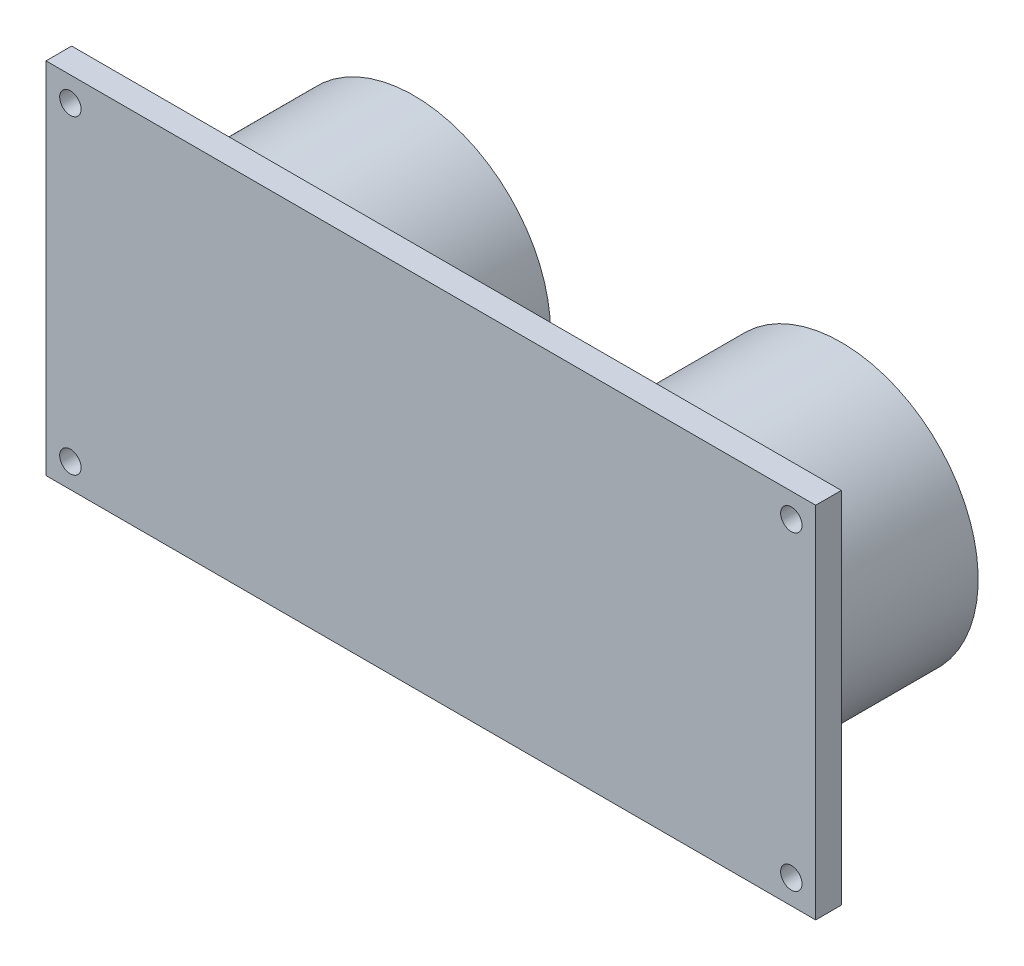
SolidWorks part; units mm, degrees
ref_plane "Alzado" through (0, 0, 0) normal (0, 0, 1) x (1, 0, 0)
ref_plane "Planta" through (0, 0, 0) normal (0, 1, 0) x (1, 0, 0)
ref_plane "Vista lateral" through (0, 0, 0) normal (1, 0, 0) x (0, 0, -1)
sketch "Croquis1" plane through (0, 0, 0) normal (0, 0, 1) x (1, 0, 0)
  line L0 (0.8, 0.8) -> (44.2, 0.8) construction
  line L1 (0, 0) -> (45, 0)
  line L2 (0, 0) -> (0, 21)
  line L3 (0, 21) -> (45, 21)
  line L4 (45, 0) -> (45, 21)
  line L5 (44.2, 0.8) -> (44.2, 20.2) construction
  line L6 (0.8, 20.2) -> (44.2, 20.2) construction
  line L7 (0.8, 0.8) -> (0.8, 20.2) construction
  line L8 (22.5, 21) -> (22.5, 0) construction
  line L9 (0, 10.5) -> (45, 10.5) construction
  circle A0 centre (1.425, 19.575) radius 0.625
  circle A1 centre (43.575, 19.575) radius 0.625
  circle A2 centre (43.575, 1.425) radius 0.625
  circle A3 centre (1.425, 1.425) radius 0.625
  point P11 (1.425, 20.2)
  point P12 (0.8, 19.575)
  dimension "D4" = 1.25
  dimension "D1" = 45
  dimension "D2" = 21
  dimension "D3" = 0.8
extrude "Saliente-Extruir1" add sketch "Croquis1" along normal blind 1.5
sketch "Croquis2" plane through (0, 0, 0) normal (0, 0, -1) x (-1, 0, 0)
  line L0 (-45, 10.5) -> (0, 10.5) construction
  line L1 (-45, 0) -> (-45, 21) construction
  line L2 (0, 21) -> (0, 0) construction
  line L3 (-22.5, 0) -> (-22.5, 21) construction
  line L4 (0, 0) -> (-45, 0) construction
  line L5 (-45, 21) -> (0, 21) construction
  circle A0 centre (-35, 10.5) radius 8
  circle A1 centre (-10, 10.5) radius 8
  point P14 (-43, 10.5)
  dimension "D1" = 16
  dimension "D2" = 25
extrude "Saliente-Extruir2" add sketch "Croquis2" along normal blind 10
